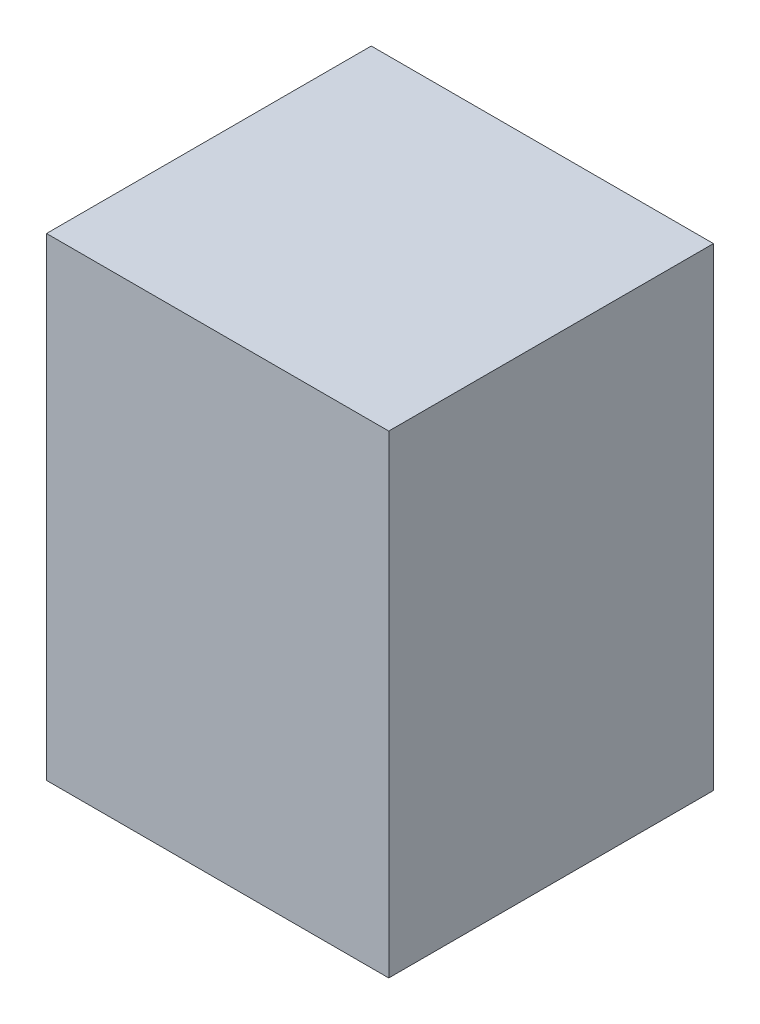
SolidWorks part; units mm, degrees
ref_plane "Front Plane" through (0, 0, 0) normal (0, 0, 1) x (1, 0, 0)
ref_plane "Top Plane" through (0, 0, 0) normal (0, 1, 0) x (1, 0, 0)
ref_plane "Right Plane" through (0, 0, 0) normal (1, 0, 0) x (0, 0, -1)
sketch "Sketch1" plane through (0, 0, 0) normal (0, 1, 0) x (1, 0, 0)
  line L1 (-39.3426, -38.505) -> (52.412, -38.505)
  line L2 (-39.3426, -38.505) -> (-39.3426, 48.5562)
  line L3 (-39.3426, 48.5562) -> (52.412, 48.5562)
  line L4 (52.412, -38.505) -> (52.412, 48.5562)
extrude "Boss-Extrude1" add sketch "Sketch1" along normal blind 127
